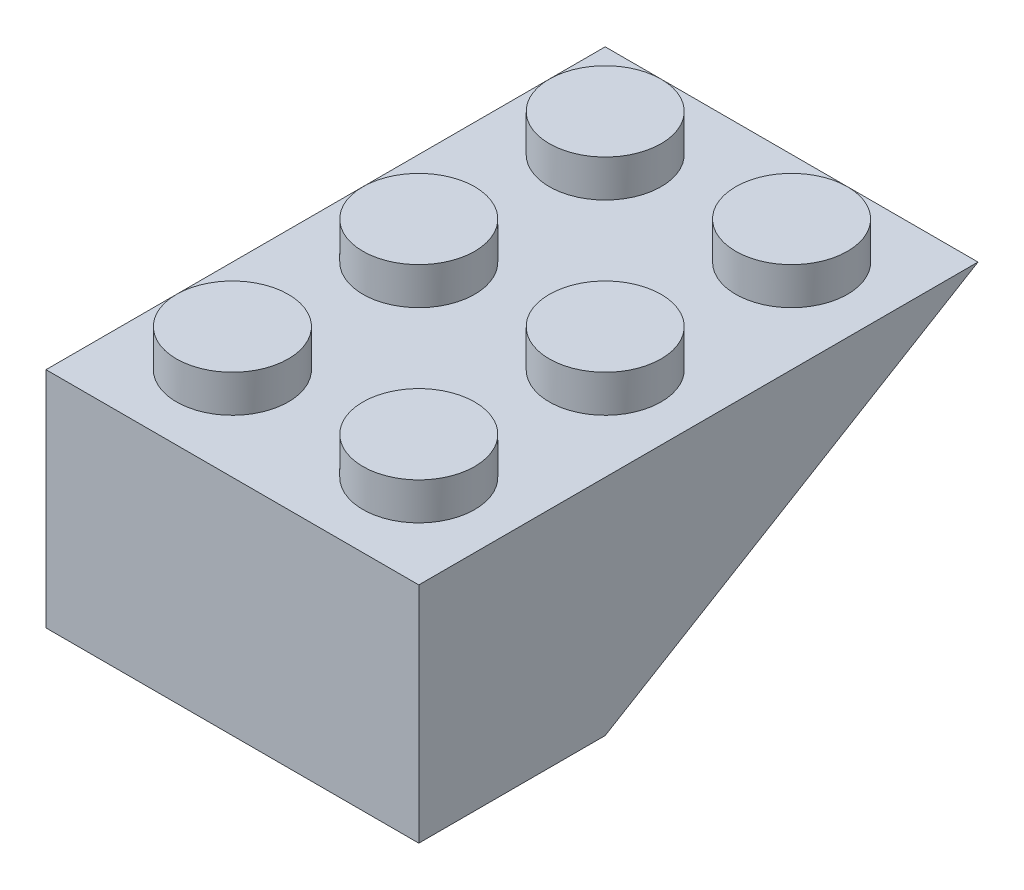
SolidWorks part; units mm, degrees
ref_plane "Front Plane" through (0, 0, 0) normal (0, 0, 1) x (1, 0, 0)
ref_plane "Top Plane" through (0, 0, 0) normal (0, 1, 0) x (1, 0, 0)
ref_plane "Right Plane" through (0, 0, 0) normal (1, 0, 0) x (0, 0, -1)
sketch "Sketch1" plane through (0, 0, 0) normal (0, 1, 0) x (1, 0, 0)
  line L1 (0, 0) -> (16, 0)
  line L2 (0, 0) -> (0, 8)
  line L3 (0, 8) -> (16, 8)
  line L4 (16, 0) -> (16, 8)
  dimension "D1" = 16
  dimension "D2" = 8
extrude "Boss-Extrude1" add sketch "Sketch1" along normal blind 9.6
shell "Shell1" thickness 1.6
sketch "Sketch3" plane through (16, 0, 0) normal (1, 0, 0) x (0, 0, -1)
  line L0 (8, 0) -> (24, 9.6)
  line L1 (24, 9.6) -> (8, 9.6)
  line L2 (8, 9.6) -> (8, 0)
  dimension "D1" = 16
extrude "Boss-Extrude3" add sketch "Sketch3" against normal blind 16
sketch "Sketch2" plane through (0, 9.6, 0) normal (0, 1, 0) x (1, 0, 0)
  line L3 (16, 0) -> (16, 4) construction
  line L4 (16, 0) -> (16, 24) construction
  line L5 (16, 4) -> (12, 4) construction
  circle A0 centre (12, 4) radius 2.4
  dimension "D3" = 4.8
  dimension "D1" = 4
  dimension "D2" = 4
extrude "Boss-Extrude2" add sketch "Sketch2" along normal blind 1.6
pattern_linear "LPattern1" count 2 spacing 8 along (-1, 0, 0) count 3 spacing 8 along (0, 0, -1) of "Boss-Extrude2"
